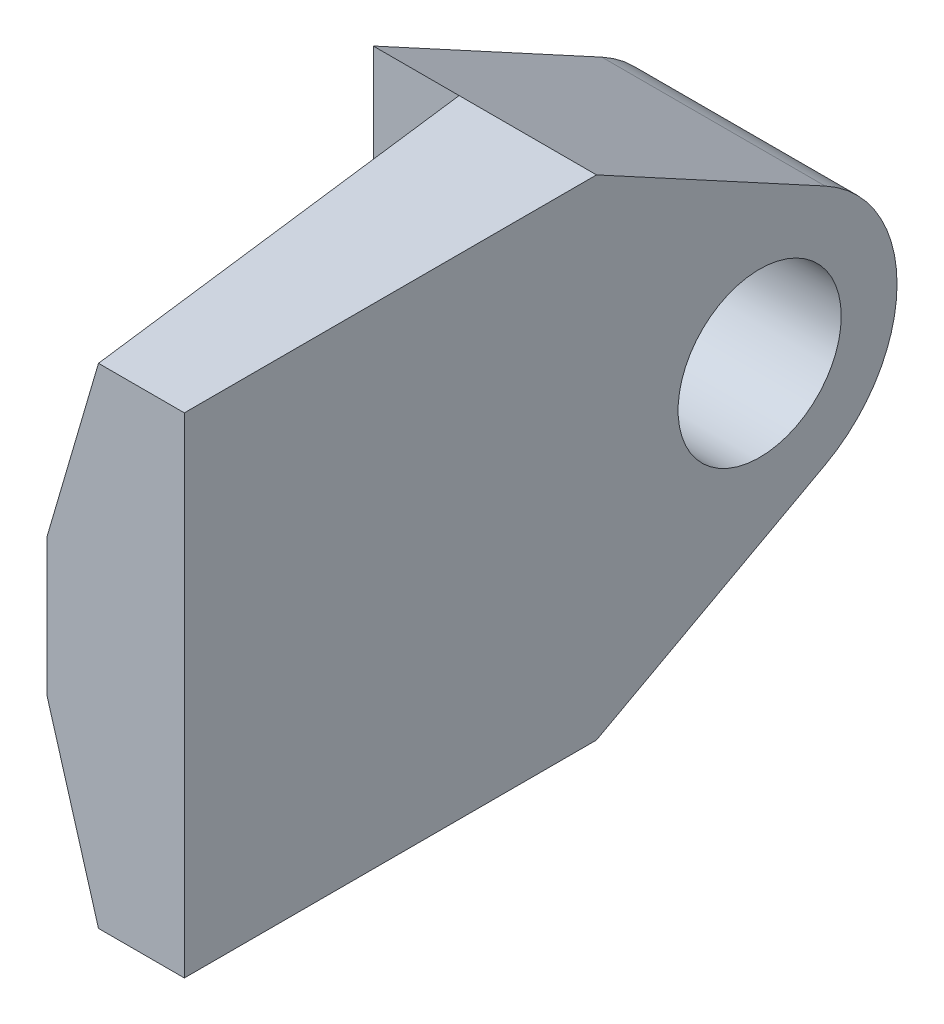
SolidWorks part; units mm, degrees
ref_plane "Front Plane" through (0, 0, 0) normal (0, 0, 1) x (1, 0, 0)
ref_plane "Top Plane" through (0, 0, 0) normal (0, 1, 0) x (1, 0, 0)
ref_plane "Right Plane" through (0, 0, 0) normal (1, 0, 0) x (0, 0, -1)
sketch "Sketch1" plane through (0, 0, 0) normal (0, 0, 1) x (1, 0, 0)
  line L0 (-20, 116.2307) -> (-20, -38.1578) construction
  line L1 (-32, 0) -> (0, 0)
  line L2 (-32, 0) -> (-32, 114)
  line L3 (-32, 114) -> (0, 114)
  line L4 (0, 0) -> (0, 114)
  line L5 (-36.1553, 41) -> (146.4358, 41) construction
  line L6 (-76.7354, 73) -> (105.8556, 73) construction
  point P11 (0, 0)
  point P12 (0, 0)
  point P13 (0, 0)
  dimension "D1" = 32
  dimension "D2" = 114
  dimension "D3" = 12
  dimension "D4" = 41
  dimension "D5" = 41
extrude "Boss-Extrude1" add sketch "Sketch1" against normal blind 96 contours L2 L3 L4 L1
ref_point "Point1" parameters "D1"=12
ref_point "Point2" parameters "D1"=41
ref_point "Point3" parameters "D1"=12
ref_point "Point4" parameters "D1"=41
ref_plane "Plane1" through (-48.4577, 14.1827, 6.0572) normal (-0.9529, 0.2789, 0.1191) x (0.1143, -0.0335, 0.9929)
ref_plane "Plane3" through (-18.1605, -5.3153, 2.2701) normal (-0.9529, -0.2789, 0.1191) x (0.1143, 0.0335, 0.9929)
sketch "Sketch3" plane through (-48.4577, 14.1827, 6.0572) normal (-0.9529, 0.2789, 0.1191) x (0.1143, -0.0335, 0.9929)
  line L0 (-6.1006, 61.0721) -> (-6.1006, 103.7921)
  line L1 (-6.1006, 103.7921) -> (-102.789, 100.4213)
  line L2 (-102.789, 100.4213) -> (-6.1006, 61.0721)
sketch "Sketch4" plane through (-18.1605, -5.3153, 2.2701) normal (-0.9529, -0.2789, 0.1191) x (0.1143, 0.0335, 0.9929)
  line L0 (-98.9747, 8.9888) -> (-2.2863, 48.338)
  line L1 (-2.2863, 48.338) -> (-2.2863, 5.618)
  line L2 (-2.2863, 5.618) -> (-98.9747, 8.9888)
extrude "Cut-Extrude1" cut sketch "Sketch4" along normal up to next
extrude "Cut-Extrude2" cut sketch "Sketch3" along normal up to next contours L2 L0 L1
sketch "Sketch8" plane through (0, 0, 0) normal (1, 0, 0) x (0, 0, -1)
  line L0 (96, 0) -> (96, 114) construction
  line L2 (96, 114) -> (149.2508, 85.1321)
  line L3 (96, 0) -> (149.2508, 28.8679)
  line L4 (230.7392, 57) -> (96, 57) construction
  line L5 (96, 0) -> (96, 114)
  circle A0 centre (134, 57) radius 19
  arc A1 (149.2508, 28.8679) -> (149.2508, 85.1321) centre (134, 57) ccw
  point P8 (0, 0)
  dimension "D1" = 38
  dimension "D3" = 32
  dimension "D2" = 38
extrude "Boss-Extrude2" add sketch "Sketch8" against normal blind 52
